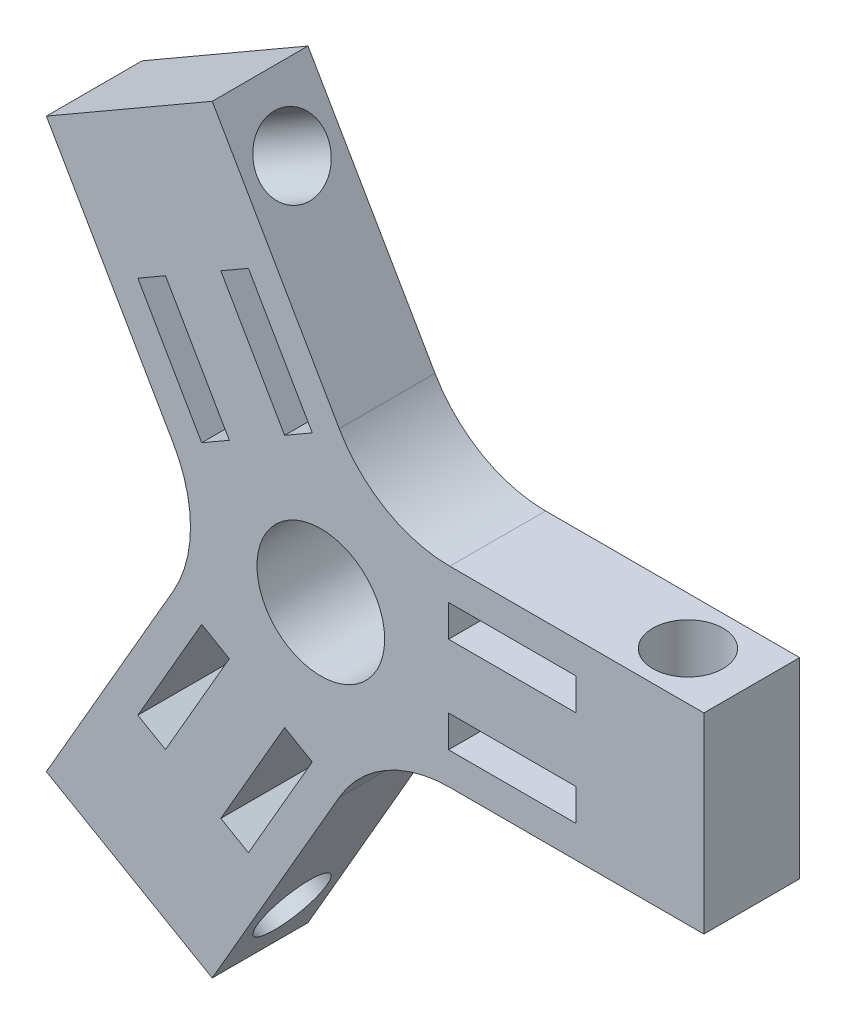
SolidWorks part; units mm, degrees
ref_plane "Plan de face" through (0, 0, 0) normal (0, 0, 1) x (1, 0, 0)
ref_plane "Plan de dessus" through (0, 0, 0) normal (0, 1, 0) x (1, 0, 0)
ref_plane "Plan de droite" through (0, 0, 0) normal (1, 0, 0) x (0, 0, -1)
sketch "Esquisse1" plane through (0, 0, 0) normal (0, 0, 1) x (1, 0, 0)
  line L0 (0, 0) -> (60, 0) construction
  line L1 (0, 0) -> (-30, -51.9615) construction
  line L2 (0, 0) -> (-30, 51.9615) construction
  line L3 (60, 0) -> (60, -15)
  line L4 (60, 0) -> (60, 15)
  line L5 (-30, -51.9615) -> (-42.9904, -44.4615)
  line L6 (-30, 51.9615) -> (-17.0096, 59.4615)
  line L7 (-30, -51.9615) -> (-17.0096, -59.4615)
  line L8 (-30, 51.9615) -> (-42.9904, 44.4615)
  line L9 (-42.9904, 44.4615) -> (-17.3205, 0)
  line L10 (-42.9904, -44.4615) -> (-17.3205, 0)
  line L11 (-17.0096, -59.4615) -> (8.6603, -15)
  line L12 (60, -15) -> (8.6603, -15)
  line L13 (60, 15) -> (8.6603, 15)
  line L14 (8.6603, 15) -> (-17.0096, 59.4615)
  point P7 (0, 0)
  point P14 (0, 0)
  point P20 (0, 0)
  dimension "D1" = 3
  dimension "D2" = 60
  dimension "D3" = 15
  dimension "D4" = 15
  dimension "D7" = 51.3397
  dimension "D5" = 3
  dimension "D6" = 3
extrude "Boss.-Extru.4" add sketch "Esquisse1" along normal blind 15
sketch "Esquisse4" plane through (0, 0, 15) normal (0, 0, 1) x (1, 0, 0)
  line L0 (-11.3397, -39.641) -> (-1.3397, -22.3205)
  line L1 (20, 10) -> (20, 5)
  line L2 (20, 5) -> (40, 5)
  line L3 (40, 5) -> (40, 10)
  line L4 (40, 10) -> (20, 10)
  line L5 (60, -15) -> (60, 15) construction
  line L6 (40, -5) -> (40, -10)
  line L7 (20, -5) -> (40, -5)
  line L8 (20, -10) -> (20, -5)
  line L9 (40, -10) -> (20, -10)
  line L10 (-1.3397, -22.3205) -> (-5.6699, -19.8205)
  line L11 (-5.6699, -19.8205) -> (-15.6699, -37.141)
  line L12 (-15.6699, -37.141) -> (-11.3397, -39.641)
  line L13 (-24.3301, -32.141) -> (-28.6603, -29.641)
  line L14 (-28.6603, -29.641) -> (-18.6603, -12.3205)
  line L15 (-18.6603, -12.3205) -> (-14.3301, -14.8205)
  line L16 (-14.3301, -14.8205) -> (-24.3301, -32.141)
  line L17 (-28.6603, 29.641) -> (-18.6603, 12.3205)
  line L18 (-18.6603, 12.3205) -> (-14.3301, 14.8205)
  line L19 (-14.3301, 14.8205) -> (-24.3301, 32.141)
  line L20 (-24.3301, 32.141) -> (-28.6603, 29.641)
  line L21 (-15.6699, 37.141) -> (-11.3397, 39.641)
  line L22 (-11.3397, 39.641) -> (-1.3397, 22.3205)
  line L23 (-1.3397, 22.3205) -> (-5.6699, 19.8205)
  line L24 (-5.6699, 19.8205) -> (-15.6699, 37.141)
  circle A0 centre (0, 0) radius 10
  point P31 (0, 0)
  dimension "D1" = 3
  dimension "D2" = 5
  dimension "D3" = 20
  dimension "D4" = 20
extrude "Enlèv. mat.-Extru.3" cut sketch "Esquisse4" against normal blind 15
sketch "Esquisse5" plane through (12.9904, -7.5, 0) normal (0.866, -0.5, 0) x (0, 0, -1)
  line L0 (-15, -60) -> (0, -60) construction
  line L1 (0, -60) -> (0, -8.6603) construction
  circle A0 centre (-7.5, -50) radius 5.5
  dimension "D1" = 10
  dimension "D2" = 7.5
extrude "Enlèv. mat.-Extru.4" cut sketch "Esquisse5" against normal blind 50
fillet "Congé10" radius 20 1 edges at (8.6603, -15, 7.5)
fillet "Congé11" radius 20 1 edges at (8.6603, 15, 7.5)
fillet "Congé12" radius 20 1 edges at (-17.3205, 0, 7.5)
sketch "Esquisse6" plane through (12.9904, 7.5, 0) normal (0.866, 0.5, 0) x (0, 0, -1)
  line L0 (-15, 60) -> (0, 60) construction
  line L1 (0, 20.2073) -> (0, 60) construction
  circle A0 centre (-7.5, 50) radius 5.5
  dimension "D1" = 10
  dimension "D2" = 7.5
extrude "Enlèv. mat.-Extru.5" cut sketch "Esquisse6" against normal blind 50
sketch "Esquisse7" plane through (0, 15, 0) normal (0, 1, 0) x (1, 0, 0)
  line L0 (60, -15) -> (60, 0) construction
  line L1 (60, -15) -> (20.2073, -15) construction
  circle A0 centre (50, -7.5) radius 5.5
  dimension "D1" = 10
  dimension "D2" = 7.5
extrude "Enlèv. mat.-Extru.6" cut sketch "Esquisse7" against normal blind 50
